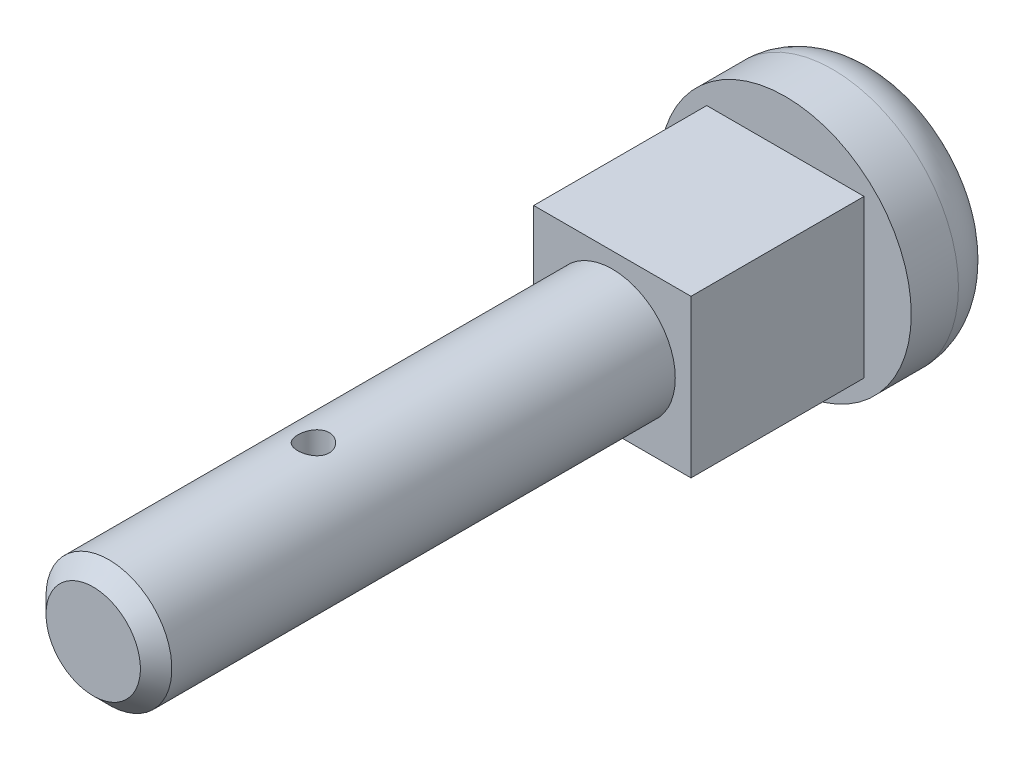
SolidWorks part; units mm, degrees
ref_plane "Front Plane" through (0, 0, 0) normal (0, 0, 1) x (1, 0, 0)
ref_plane "Top Plane" through (0, 0, 0) normal (0, 1, 0) x (1, 0, 0)
ref_plane "Right Plane" through (0, 0, 0) normal (1, 0, 0) x (0, 0, -1)
sketch "Sketch1" plane through (0, 0, 0) normal (0, 0, 1) x (1, 0, 0)
  circle A0 centre (0, 0) radius 8
  dimension "D1" = 16
extrude "Boss-Extrude1" add sketch "Sketch1" against normal blind 6
sketch "Sketch2" plane through (0, 0, 0) normal (0, 0, 1) x (1, 0, 0)
  line L1 (5, -5) -> (-5, -5)
  line L2 (5, -5) -> (5, 5)
  line L3 (5, 5) -> (-5, 5)
  line L4 (-5, -5) -> (-5, 5)
  line L5 (5, -5) -> (-5, 5) construction
  line L6 (5, 5) -> (-5, -5) construction
  point P0 (0, 0)
  dimension "D1" = 10
extrude "Boss-Extrude2" add sketch "Sketch2" along normal blind 11
sketch "Sketch4" plane through (0, 0, 0) normal (0, 0, 1) x (1, 0, 0)
  circle A0 centre (0, 0) radius 4
  dimension "D1" = 8
extrude "Boss-Extrude3" add sketch "Sketch4" along normal blind 44
hole_wizard "Ø2.0 (2) Diameter Hole1" positions "3DSketch1" profile "Sketch5" hole size "Ø2.0" standard "ISO" end condition through all
sketch3d "3DSketch1"
  point P0 (0, 4, 30)
  dimension "D1" = 30
  dimension "D2" = 0
sketch "Sketch5" plane through (0, 4, 30) normal (1, 0, 0) x (0, 0, 1)
  line L0 (0, 0) -> (0, 12)
  line L1 (0, 12) -> (1, 12)
  line L2 (1, 12) -> (1, 0)
  line L5 (1, 0) -> (0, 0)
  line L11 (0, -6.35) -> (0, 107.95) construction
  dimension "Thru Hole Dia." = 2
  dimension "Thru Hole Depth" = 12
fillet "Fillet1" radius 3 1 edges at (8, 0, -6)
chamfer "Chamfer1" distance 1 angle 45 1 edges at (4, 0, 44)
